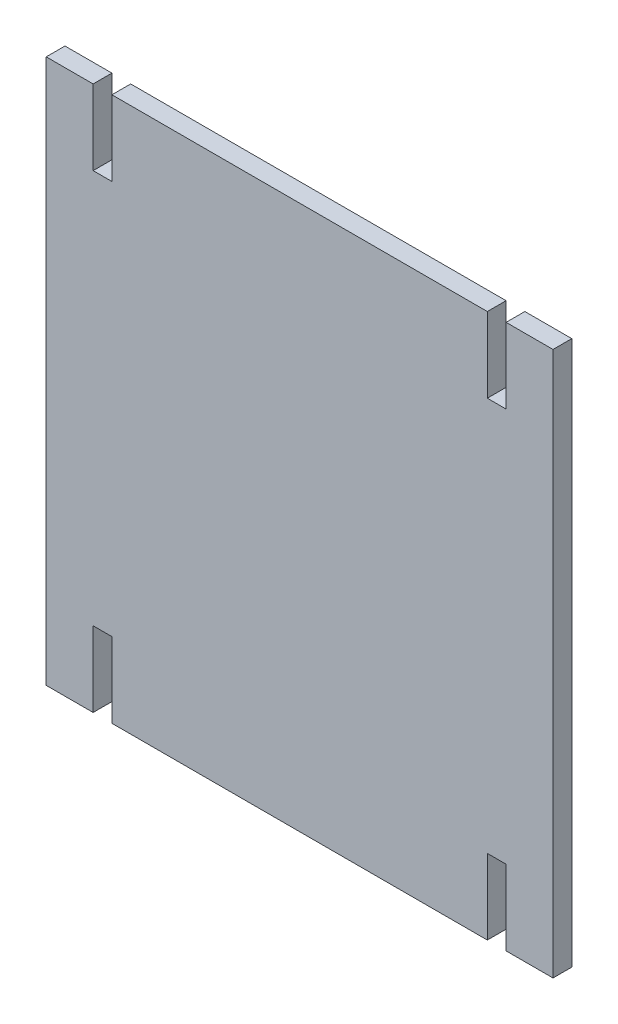
SolidWorks part; units mm, degrees
ref_plane "Front Plane" through (0, 0, 0) normal (0, 0, 1) x (1, 0, 0)
ref_plane "Top Plane" through (0, 0, 0) normal (0, 1, 0) x (1, 0, 0)
ref_plane "Right Plane" through (0, 0, 0) normal (1, 0, 0) x (0, 0, -1)
sketch "Sketch1" plane through (0, 0, 0) normal (0, 0, 1) x (1, 0, 0)
  line L0 (0, 0) -> (0, -10.16)
  line L1 (0, -73.66) -> (50.8, -73.66)
  line L2 (50.8, -73.66) -> (50.8, -63.5)
  line L3 (50.8, 0) -> (0, 0)
  line L4 (0, -10.16) -> (-2.54, -10.16)
  line L5 (-2.54, -10.16) -> (-2.54, 0)
  line L6 (-2.54, 0) -> (-8.89, 0)
  line L7 (-8.89, 0) -> (-8.89, -73.66)
  line L8 (-8.89, -73.66) -> (-2.54, -73.66)
  line L9 (-2.54, -73.66) -> (-2.54, -63.5)
  line L10 (0, -63.5) -> (-2.54, -63.5)
  line L11 (0, -73.66) -> (0, -63.5)
  line L12 (50.8, -63.5) -> (53.34, -63.5)
  line L13 (53.34, -63.5) -> (53.34, -73.66)
  line L14 (53.34, -73.66) -> (59.69, -73.66)
  line L15 (59.69, -73.66) -> (59.69, 0)
  line L16 (59.69, 0) -> (53.34, 0)
  line L17 (53.34, 0) -> (53.34, -10.16)
  line L18 (53.34, -10.16) -> (50.8, -10.16)
  line L19 (50.8, -10.16) -> (50.8, 0)
  dimension "D1" = 10.16
extrude "Boss-Extrude1" add sketch "Sketch1" along normal blind 2.54
sketch "Sketch2" plane through (59.69, 0, 0) normal (1, 0, 0) x (0, 0, -1)
  line L0 (-2.54, 0) -> (0, 0) construction
  line L1 (-2.54, -73.66) -> (-2.54, 0) construction
  point P0 (-1.27, -36.83)
  point P3 (-1.27, 0)
  point P6 (-2.54, -36.83)
ref_plane "Plane1" through (0, -36.83, 0) normal (0, 1, 0) x (1, 0, 0)
sketch "Sketch3" plane through (0, -36.83, 0) normal (0, 1, 0) x (1, 0, 0)
  line L0 (59.8937, -1.27) -> (62.7, -1.27) construction
